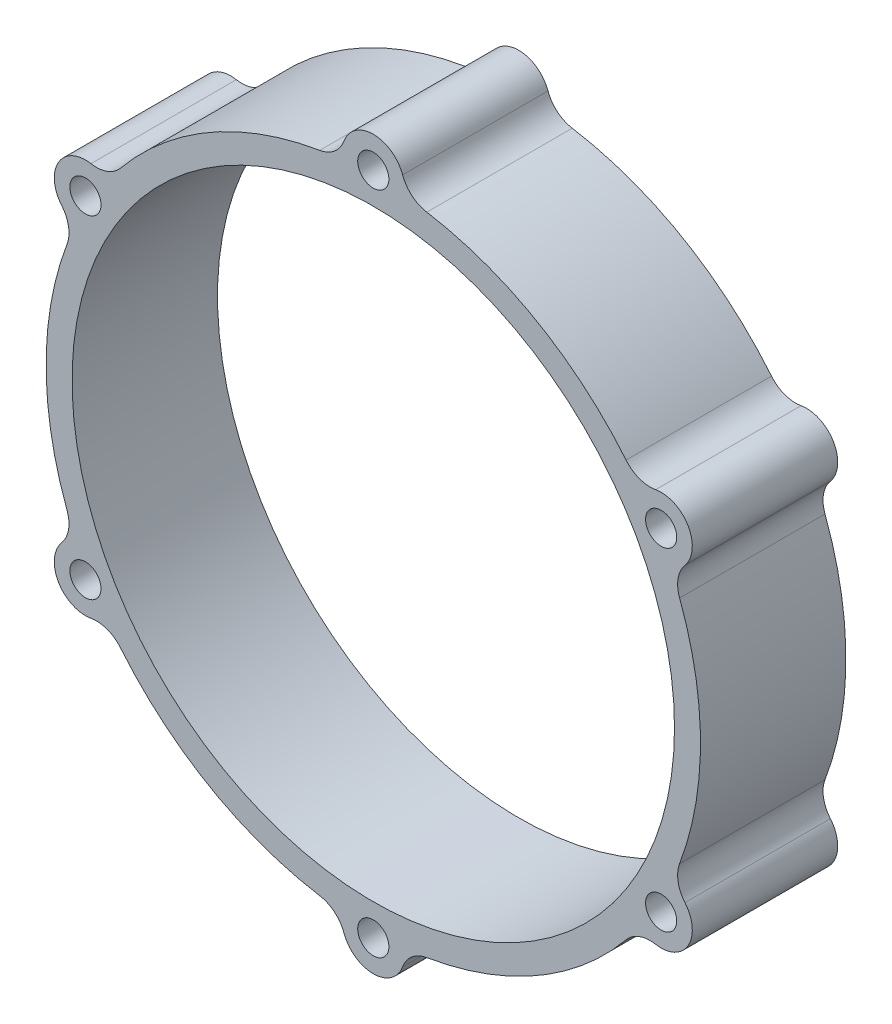
SolidWorks part; units mm, degrees
material "6061 合金"
ref_plane "前视基准面" through (0, 0, 0) normal (0, 0, 1) x (1, 0, 0)
ref_plane "上视基准面" through (0, 0, 0) normal (0, 1, 0) x (1, 0, 0)
ref_plane "右视基准面" through (0, 0, 0) normal (1, 0, 0) x (0, 0, -1)
sketch "草图1" plane through (0, 0, 0) normal (0, 0, 1) x (1, 0, 0)
  circle A0 centre (0, 0) radius 31.5
  circle A1 centre (0, 0) radius 29
  dimension "D1" = 58
  dimension "D2" = 63
extrude "凸台-拉伸1" add sketch "草图1" along normal blind 14
sketch "草图2" plane through (0, 0, 14) normal (0, 0, 1) x (1, 0, 0)
  line L1 (0, 32) -> (-27.7128, 16) construction
  line L2 (-27.7128, 16) -> (-27.7128, -16) construction
  line L3 (-27.7128, -16) -> (0, -32) construction
  line L4 (0, -32) -> (27.7128, -16) construction
  line L5 (27.7128, -16) -> (27.7128, 16) construction
  line L6 (27.7128, 16) -> (0, 32) construction
  circle A1 centre (0, 0) radius 32 construction
  arc A2 (2.9317, 31.3633) -> (-2.9317, 31.3633) centre (0, 32) ccw
  arc A3 (28.6272, 13.1428) -> (25.6956, 18.2205) centre (27.7128, 16) ccw
  arc A4 (25.6956, -18.2205) -> (28.6272, -13.1428) centre (27.7128, -16) ccw
  arc A5 (-2.9317, -31.3633) -> (2.9317, -31.3633) centre (0, -32) ccw
  arc A6 (-28.6272, -13.1428) -> (-25.6956, -18.2205) centre (-27.7128, -16) ccw
  arc A7 (-25.6956, 18.2205) -> (-28.6272, 13.1428) centre (-27.7128, 16) ccw
  circle A8 centre (0, 0) radius 31.5 construction
  circle A9 centre (0, 0) radius 31.5 construction
  arc A10 (-2.9317, 31.3633) -> (2.9317, 31.3633) centre (0, 0) cw
  arc A11 (25.6956, 18.2205) -> (28.6272, 13.1428) centre (0, 0) cw
  arc A12 (-25.6956, 18.2205) -> (-28.6272, 13.1428) centre (0, 0) ccw
  arc A13 (-28.6272, -13.1428) -> (-25.6956, -18.2205) centre (0, 0) ccw
  arc A14 (-2.9317, -31.3633) -> (2.9317, -31.3633) centre (0, 0) ccw
  arc A15 (25.6956, -18.2205) -> (28.6272, -13.1428) centre (0, 0) ccw
  circle M1 centre (0, 0) radius 31.5
  dimension "D2" = 64
  dimension "D1" = 6
extrude "凸台-拉伸2" add sketch "草图2" against normal up to surface (14 mm away) contours A7 M1 | A2 M1 | A3 M1 | A4 M1 | A5 M1 | A6 M1 up to face at (31.5, 0, 0)
sketch "草图3" plane through (0, 0, 14) normal (0, 0, 1) x (1, 0, 0)
  circle A0 centre (0, 32) radius 1.5
  circle A1 centre (-27.7128, 16) radius 1.5
  circle A2 centre (-27.7128, -16) radius 1.5
  circle A3 centre (0, -32) radius 1.5
  circle A4 centre (27.7128, -16) radius 1.5
  circle A5 centre (27.7128, 16) radius 1.5
  dimension "D1" = 3
extrude "切除-拉伸1" cut sketch "草图3" against normal through all
fillet "圆角1" radius 3 12 edges at (-28.6272, 13.1428, 7) (-25.6956, 18.2205, 7) (-25.6956, -18.2205, 7) (-28.6272, -13.1428, 7) (2.9317, -31.3633, 7) (-2.9317, -31.3633, 7) (28.6272, -13.1428, 7) (25.6956, -18.2205, 7) (25.6956, 18.2205, 7) (28.6272, 13.1428, 7) (-2.9317, 31.3633, 7) (2.9317, 31.3633, 7)
